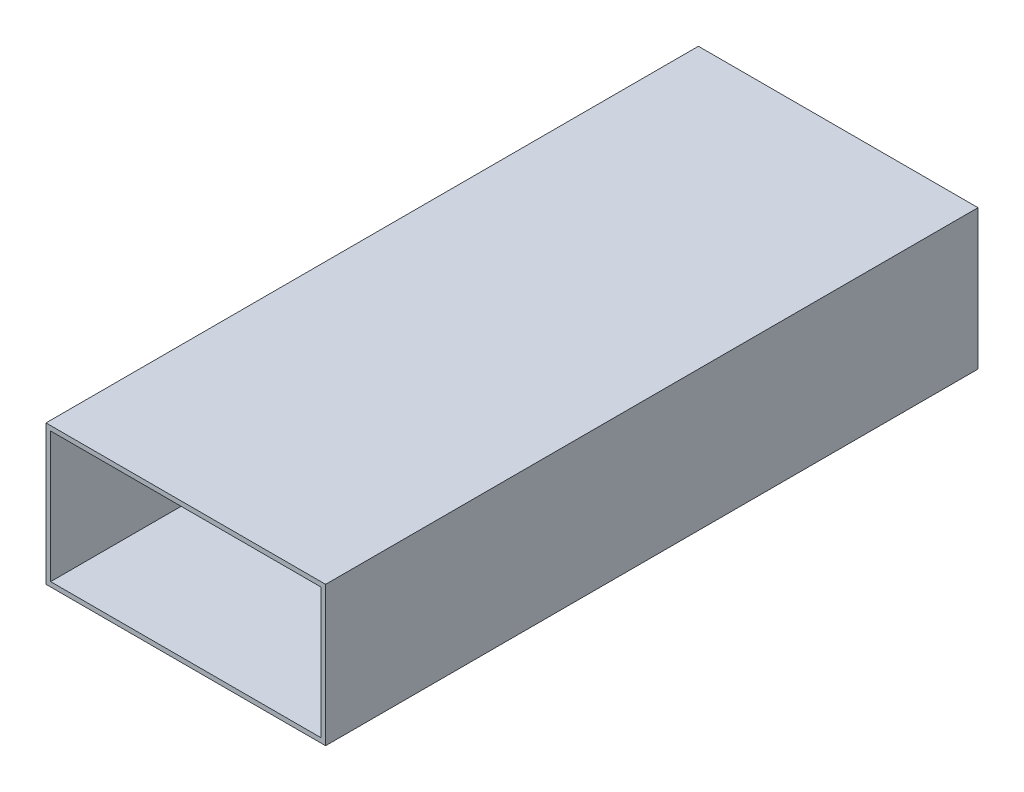
SolidWorks part; units mm, degrees
material "1100-H12 棒材(SS)"
ref_plane "前视基准面" through (0, 0, 0) normal (0, 0, 1) x (1, 0, 0)
ref_plane "上视基准面" through (0, 0, 0) normal (0, 1, 0) x (1, 0, 0)
ref_plane "右视基准面" through (0, 0, 0) normal (1, 0, 0) x (0, 0, -1)
other "Configuration Table"
sketch "草图1" plane through (0, 0, 0) normal (0, 0, 1) x (1, 0, 0)
  line L1 (0, 0) -> (60, 0)
  line L2 (0, 0) -> (0, 30)
  line L3 (0, 30) -> (60, 30)
  line L4 (60, 0) -> (60, 30)
  line L5 (1, 1) -> (59, 1)
  line L6 (1, 1) -> (1, 29)
  line L7 (1, 29) -> (59, 29)
  line L8 (59, 1) -> (59, 29)
  dimension "D1" = 60
  dimension "D2" = 30
  dimension "D3" = 1
  dimension "D4" = 1
  dimension "D5" = 1
  dimension "D6" = 1
extrude "凸台-拉伸1" add sketch "草图1" along normal blind 140
